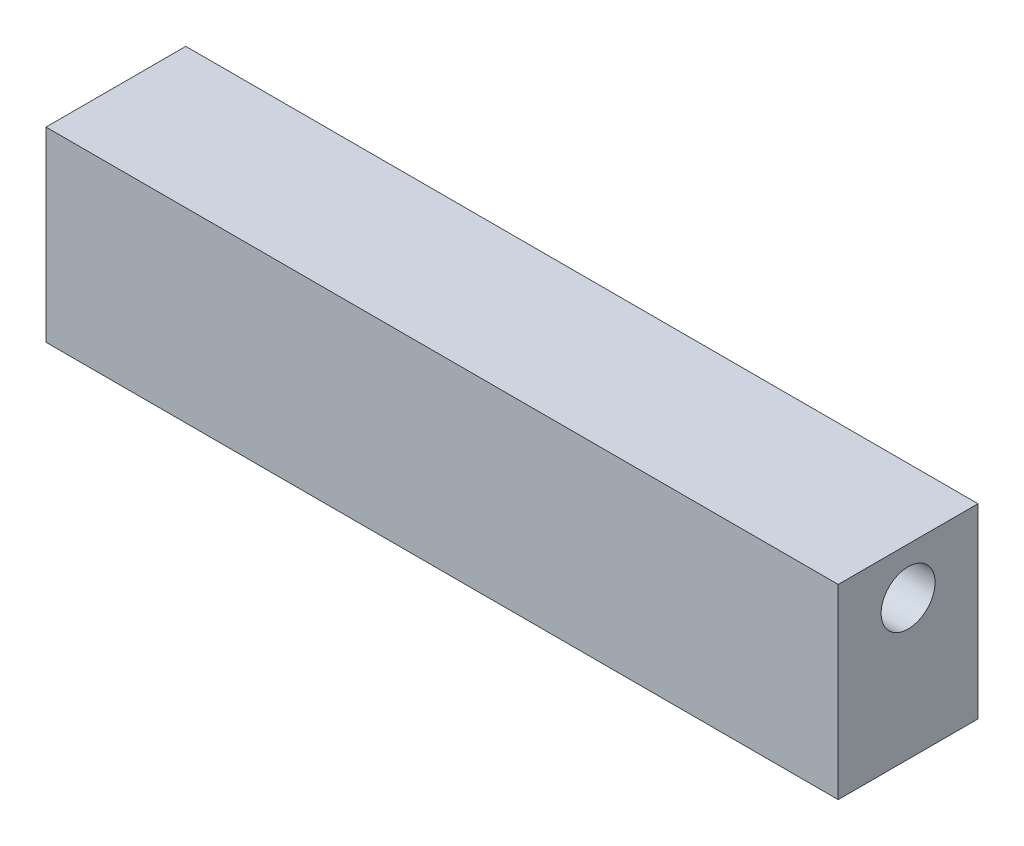
SolidWorks part; units mm, degrees
ref_plane "Front Plane" through (0, 0, 0) normal (0, 0, 1) x (1, 0, 0)
ref_plane "Top Plane" through (0, 0, 0) normal (0, 1, 0) x (1, 0, 0)
ref_plane "Right Plane" through (0, 0, 0) normal (1, 0, 0) x (0, 0, -1)
sketch "Sketch2" plane through (0, 0, 0) normal (0, 1, 0) x (1, 0, 0)
  line L1 (0, 0) -> (170, 0)
  line L2 (0, 0) -> (0, 30)
  line L3 (0, 30) -> (170, 30)
  line L4 (170, 0) -> (170, 30)
extrude "Boss-Extrude1" add sketch "Sketch2" along normal blind 40
sketch "Sketch3" plane through (0, 0, 0) normal (0, -1, 0) x (1, 0, 0)
  line L1 (10, -10) -> (160, -10)
  line L2 (10, -10) -> (10, -20)
  line L3 (10, -20) -> (160, -20)
  line L4 (160, -10) -> (160, -20)
extrude "Cut-Extrude1" cut sketch "Sketch3" against normal blind 20
sketch "Sketch4" plane through (170, 0, 0) normal (1, 0, 0) x (0, 0, -1)
  circle A0 centre (15, 30) radius 5.7891
extrude "Cut-Extrude2" cut sketch "Sketch4" against normal blind 170 contours A0
